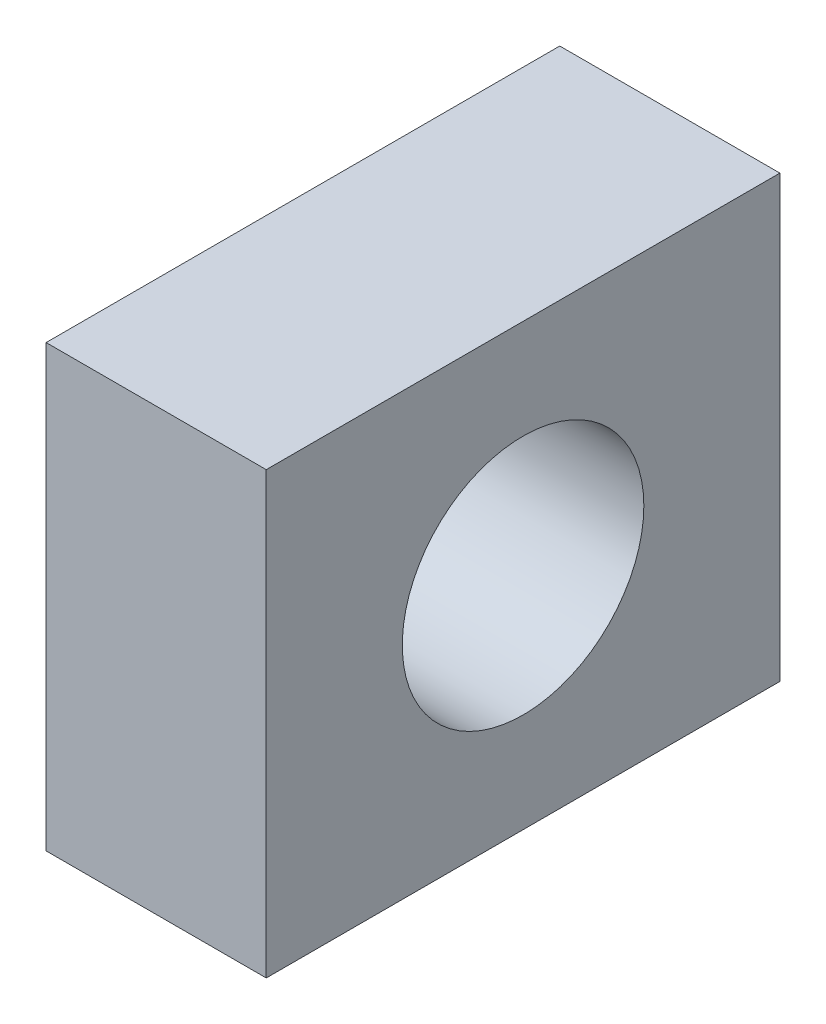
SolidWorks part; units mm, degrees
ref_plane "Front Plane" through (0, 0, 0) normal (0, 0, 1) x (1, 0, 0)
ref_plane "Top Plane" through (0, 0, 0) normal (0, 1, 0) x (1, 0, 0)
ref_plane "Right Plane" through (0, 0, 0) normal (1, 0, 0) x (0, 0, -1)
sketch "Sketch1" plane through (0, 0, 0) normal (1, 0, 0) x (0, 0, -1)
  line L1 (-17.5, 15) -> (17.5, 15)
  line L2 (-17.5, 15) -> (-17.5, -15)
  line L3 (-17.5, -15) -> (17.5, -15)
  line L4 (17.5, 15) -> (17.5, -15)
  line L5 (-17.5, 15) -> (17.5, -15) construction
  line L6 (-17.5, -15) -> (17.5, 15) construction
  point P0 (0, 0)
  dimension "D1" = 30
  dimension "D2" = 35
extrude "Boss-Extrude1" add sketch "Sketch1" along normal blind 25
sketch "Sketch2" plane through (25, 0, 0) normal (1, 0, 0) x (0, 0, -1)
  circle A0 centre (0, 0) radius 8.23
extrude "Cut-Extrude1" cut sketch "Sketch2" against normal blind 51
sketch "Sketch3" plane through (25, 0, 0) normal (1, 0, 0) x (0, 0, -1)
  line L1 (-17.5, 15) -> (17.5, 15)
  line L2 (-17.5, 15) -> (-17.5, -15)
  line L3 (-17.5, -15) -> (17.5, -15)
  line L4 (17.5, 15) -> (17.5, -15)
  line L5 (-17.5, 15) -> (17.5, -15) construction
  line L6 (-17.5, -15) -> (17.5, 15) construction
  point P0 (0, 0)
extrude "Cut-Extrude2" cut sketch "Sketch3" against normal blind 5
sketch "Sketch4" plane through (20, 0, 0) normal (1, 0, 0) x (0, 0, -1)
  line L2 (-17.5, 15) -> (17.5, 15)
  line L3 (-17.5, 15) -> (-17.5, -15)
  line L4 (-17.5, -15) -> (17.5, -15)
  line L5 (17.5, 15) -> (17.5, -15)
  line L6 (-17.5, 15) -> (17.5, -15) construction
  line L7 (-17.5, -15) -> (17.5, 15) construction
  point P2 (0, 0)
extrude "Cut-Extrude3" cut sketch "Sketch4" against normal blind 5
